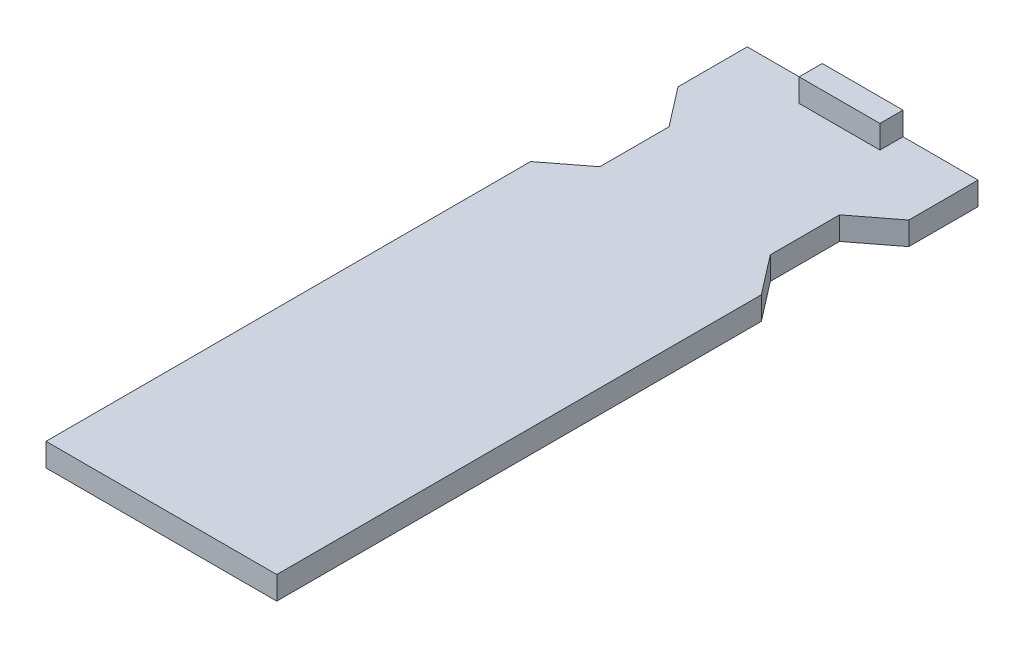
SolidWorks part; units mm, degrees
ref_plane "Front Plane" through (0, 0, 0) normal (0, 0, 1) x (1, 0, 0)
ref_plane "Top Plane" through (0, 0, 0) normal (0, 1, 0) x (1, 0, 0)
ref_plane "Right Plane" through (0, 0, 0) normal (1, 0, 0) x (0, 0, -1)
sketch "Sketch1" plane through (0, 0, 0) normal (0, 1, 0) x (1, 0, 0)
  line L0 (36.2228, 108.6683) -> (173.4812, 108.6683) construction
  line L1 (0.7793, 60) -> (0.7793, 54)
  line L2 (0.7793, 54) -> (3.3897, 50.6103)
  line L3 (3.3897, 50.6103) -> (3.3897, 44.6103)
  line L4 (3.3897, 44.6103) -> (0, 42)
  line L5 (0, 42) -> (0, 0)
  line L6 (0, 0) -> (20, 0)
  line L7 (20, 0) -> (20, 42)
  line L8 (20, 42) -> (17.3897, 45.3897)
  line L9 (17.3897, 45.3897) -> (17.3897, 51.3897)
  line L10 (17.3897, 51.3897) -> (20.7793, 54)
  line L11 (20.7793, 54) -> (20.7793, 60)
  line L12 (20.7793, 60) -> (0.7793, 60)
  dimension "D1" = 60
  dimension "D2" = 20
  dimension "D3" = 14
  dimension "D4" = 6
  dimension "D5" = 6
extrude "Boss-Extrude1" add sketch "Sketch1" along normal blind 2 contours L7 L8 L9 L10 L11 L12 L1 L2 L3 L4 L5 L6
sketch "Sketch2" plane through (0, 2, 0) normal (0, 1, 0) x (1, 0, 0)
  line L0 (20.7793, 60) -> (0.7793, 60) construction
  line L1 (7.2793, 60) -> (14.2793, 60)
  line L2 (7.2793, 60) -> (7.2793, 58)
  line L3 (7.2793, 58) -> (14.2793, 58)
  line L4 (14.2793, 60) -> (14.2793, 58)
  point P6 (10.7793, 60)
  point P7 (10.7793, 60)
  dimension "D1" = 2
  dimension "D2" = 7
extrude "Boss-Extrude2" add sketch "Sketch2" along normal blind 2 separate body
